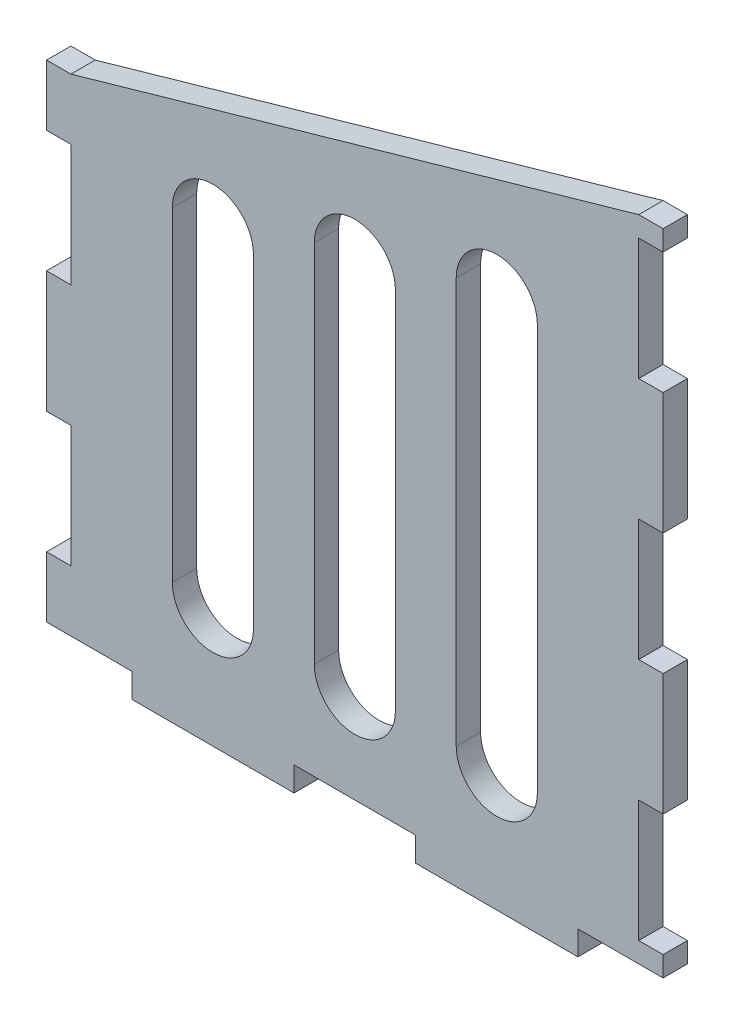
SolidWorks part; units mm, degrees
ref_plane "Front Plane" through (0, 0, 0) normal (0, 0, 1) x (1, 0, 0)
ref_plane "Top Plane" through (0, 0, 0) normal (0, 1, 0) x (1, 0, 0)
ref_plane "Right Plane" through (0, 0, 0) normal (1, 0, 0) x (0, 0, -1)
sketch "Sketch1" plane through (0, 0, 0) normal (0, 0, 1) x (1, 0, 0)
  line L0 (-35, 20) -> (35, 40)
  line L1 (38, -40) -> (-38, -40)
  line L2 (38, -40) -> (38, 40)
  line L3 (38, 40) -> (-38, 40)
  line L4 (-38, -40) -> (-38, 40)
  line L5 (38, -40) -> (-38, 40) construction
  line L6 (38, 40) -> (-38, -40) construction
  line L7 (-38, 20) -> (-35, 20)
  line L8 (35, 22.5) -> (38, 22.5)
  line L9 (35, 22.5) -> (35, 37.5)
  line L10 (35, 37.5) -> (38, 37.5)
  line L11 (38, 22.5) -> (38, 37.5)
  line L12 (35, 22.5) -> (38, 37.5) construction
  line L13 (35, 37.5) -> (38, 22.5) construction
  line L14 (35, -7.5) -> (38, -7.5)
  line L15 (35, -7.5) -> (35, 7.5)
  line L16 (35, 7.5) -> (38, 7.5)
  line L17 (38, -7.5) -> (38, 7.5)
  line L18 (35, -7.5) -> (38, 7.5) construction
  line L19 (35, 7.5) -> (38, -7.5) construction
  line L20 (-35, -32.5) -> (-38, -32.5)
  line L21 (-35, -32.5) -> (-35, -17.5)
  line L22 (-35, -17.5) -> (-38, -17.5)
  line L23 (-38, -32.5) -> (-38, -17.5)
  line L24 (-35, -32.5) -> (-38, -17.5) construction
  line L25 (-35, -17.5) -> (-38, -32.5) construction
  line L26 (27.5, -43) -> (7.5, -43)
  line L27 (27.5, -43) -> (27.5, -40)
  line L28 (27.5, -40) -> (7.5, -40)
  line L29 (7.5, -43) -> (7.5, -40)
  line L30 (27.5, -43) -> (7.5, -40) construction
  line L31 (27.5, -40) -> (7.5, -43) construction
  line L32 (-7.5, -43) -> (-27.5, -43)
  line L33 (-7.5, -43) -> (-7.5, -40)
  line L34 (-7.5, -40) -> (-27.5, -40)
  line L35 (-27.5, -43) -> (-27.5, -40)
  line L36 (-7.5, -43) -> (-27.5, -40) construction
  line L37 (-7.5, -40) -> (-27.5, -43) construction
  line L38 (35, -37.5) -> (38, -37.5)
  line L39 (35, -37.5) -> (35, -22.5)
  line L40 (35, -22.5) -> (38, -22.5)
  line L41 (38, -37.5) -> (38, -22.5)
  line L42 (35, -37.5) -> (38, -22.5) construction
  line L43 (35, -22.5) -> (38, -37.5) construction
  line L44 (-35, -2.5) -> (-38, -2.5)
  line L45 (-35, -2.5) -> (-35, 12.5)
  line L46 (-35, 12.5) -> (-38, 12.5)
  line L47 (-38, -2.5) -> (-38, 12.5)
  line L48 (-35, -2.5) -> (-38, 12.5) construction
  line L49 (-35, 12.5) -> (-38, -2.5) construction
  line L50 (-17.5, -28) -> (-17.5, 12) construction
  line L51 (-22.5, -28) -> (-22.5, 12)
  line L52 (-12.5, -28) -> (-12.5, 12)
  line L53 (17.5, -28) -> (17.5, 22) construction
  line L54 (12.5, -28) -> (12.5, 22)
  line L55 (22.5, -28) -> (22.5, 22)
  line L56 (0, 17) -> (0, -28) construction
  line L57 (5, 17) -> (5, -28)
  line L58 (-5, 17) -> (-5, -28)
  arc A0 (-22.5, -28) -> (-12.5, -28) centre (-17.5, -28) ccw
  arc A1 (-12.5, 12) -> (-22.5, 12) centre (-17.5, 12) ccw
  arc A2 (12.5, -28) -> (22.5, -28) centre (17.5, -28) ccw
  arc A3 (22.5, 22) -> (12.5, 22) centre (17.5, 22) ccw
  arc A4 (5, 17) -> (-5, 17) centre (0, 17) ccw
  arc A5 (-5, -28) -> (5, -28) centre (0, -28) ccw
  point P0 (0, 0)
  point P8 (36.5, 30)
  point P13 (36.5, 0)
  point P18 (-36.5, -25)
  point P23 (17.5, -41.5)
  point P28 (-17.5, -41.5)
  point P33 (-36.5, 5)
  point P34 (36.5, -30)
  point P46 (-17.5, -8)
  point P51 (17.5, -3)
  point P60 (0, -5.5)
  point P65 (0, 0)
  dimension "D17" = 5
  dimension "D18" = 5
  dimension "D21" = 5
  dimension "D1" = 76
  dimension "D2" = 80
  dimension "D3" = 3
  dimension "D4" = 60
  dimension "D5" = 3
  dimension "D6" = 15
  dimension "D7" = 15
  dimension "D8" = 15
  dimension "D9" = 3
  dimension "D10" = 15
  dimension "D11" = 7.5
  dimension "D12" = 3
  dimension "D13" = 20
  dimension "D14" = 15
  dimension "D15" = 7.5
  dimension "D16" = 15
  dimension "D19" = 40
  dimension "D20" = 50
  dimension "D22" = 45
  dimension "D23" = 12
extrude "Boss-Extrude1" add sketch "Sketch1" along normal blind 3
